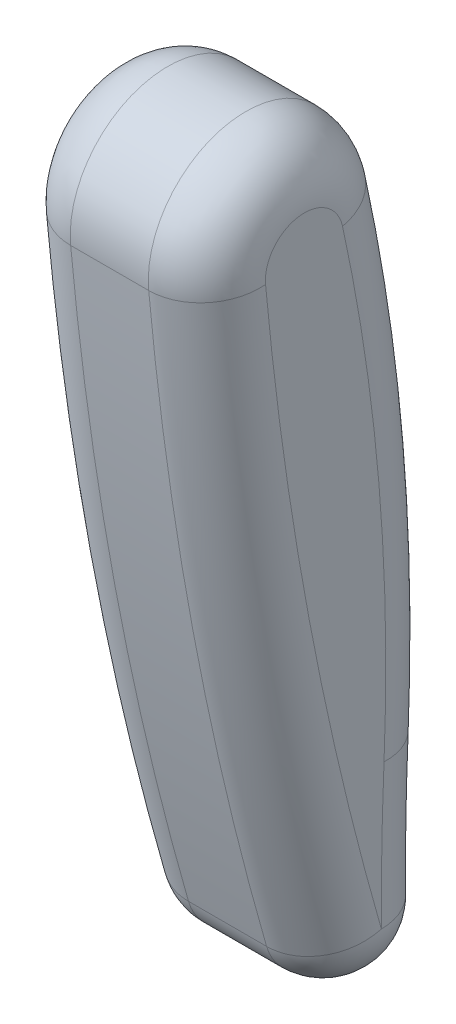
SolidWorks part; units mm, degrees
ref_plane "XY" through (0, 0, 0) normal (0, 0, 1) x (1, 0, 0)
ref_plane "YZ" through (0, 0, 0) normal (0, 1, 0) x (1, 0, 0)
ref_plane "XZ" through (0, 0, 0) normal (1, 0, 0) x (0, 0, -1)
ref_plane "Leg-plane" through (114.3, 0, 0) normal (1, 0, 0) x (0, 0, -1)
sketch "Sketch7" plane through (114.3, 0, 0) normal (1, 0, 0) x (0, 0, -1)
  line L1 (-24.1632, -755.7123) -> (25.9157, -1159.015) construction
  line L2 (0, 432.2232) -> (0, -432.2232) construction
  arc A0 (37.8855, -742.2138) -> (-87.3963, -761.529) centre (-24.1632, -755.7123) ccw
  arc A1 (-10.7018, -1169.5397) -> (64.015, -1158.7778) centre (25.9157, -1159.015) ccw
  arc A2 (-10.7018, -1169.5397) -> (-87.3963, -761.529) centre (2113.1133, -559.109) cw
  arc A3 (37.8855, -742.2138) -> (65.7157, -1067.2864) centre (-1203.0883, -1012.1842) cw
  arc A4 (64.015, -1158.7778) -> (65.7157, -1067.2864) centre (1908.0143, -1147.2947) cw
  dimension "D1" = 406.4
  dimension "D2" = 38.1
  dimension "D3" = 63.5
  dimension "D4" = 1270
  dimension "D5" = 50.8
  dimension "D6" = 2209.8
  dimension "D8" = 1844.0351
  dimension "D7" = 7.078
extrude "Base-Extrude" add sketch "Sketch7" along normal mid plane 127
fillet "Fillet1" radius 38.1 10 edges at (177.8, -1113.0215, -64.2977) (177.8, -903.8527, -62.2829) (177.8, -692.9538, 33.8389) (177.8, -967.3394, 58.6519) (50.8, -692.9538, 33.8389) (50.8, -903.8527, -62.2829) (50.8, -1113.0215, -64.2977) (50.8, -1196.7258, -31.3474) (50.8, -967.3394, 58.6519) (177.8, -1196.7258, -31.3474)
